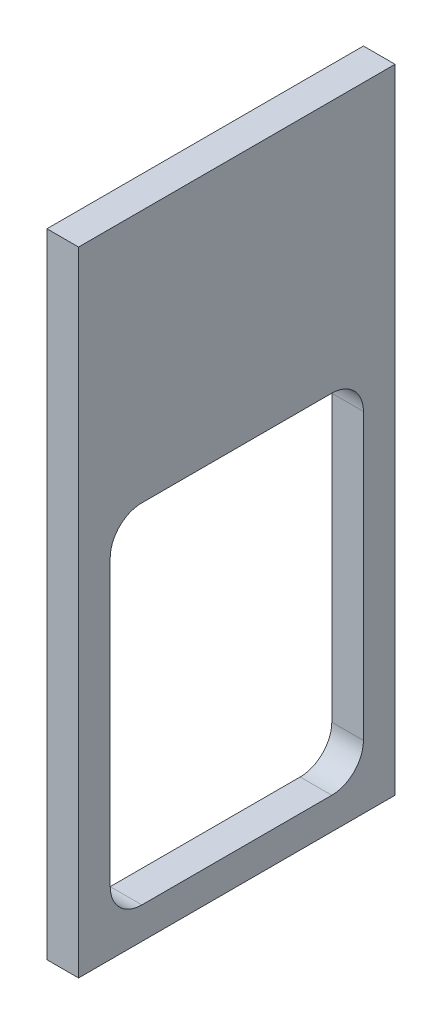
SolidWorks part; units mm, degrees
ref_plane "前视基准面" through (0, 0, 0) normal (0, 0, 1) x (1, 0, 0)
ref_plane "上视基准面" through (0, 0, 0) normal (0, 1, 0) x (1, 0, 0)
ref_plane "右视基准面" through (0, 0, 0) normal (1, 0, 0) x (0, 0, -1)
sketch "草图1" plane through (0, 0, 0) normal (1, 0, 0) x (0, 0, -1)
  line L1 (-50, -100) -> (50, -100)
  line L2 (-50, -100) -> (-50, 100)
  line L3 (-50, 100) -> (50, 100)
  line L4 (50, -100) -> (50, 100)
  line L5 (-50, -100) -> (50, 100) construction
  line L6 (-50, 100) -> (50, -100) construction
  point P0 (0, 0)
  dimension "D1" = 100
  dimension "D2" = 200
extrude "凸台-拉伸1" add sketch "草图1" along normal blind 10
sketch "草图2" plane through (10, 0, 0) normal (1, 0, 0) x (0, 0, -1)
  line L0 (50, -100) -> (50, 100) construction
  line L1 (-40, -90) -> (40, -90)
  line L2 (-40, -90) -> (-40, 20)
  line L3 (-40, 20) -> (40, 20)
  line L4 (40, -90) -> (40, 20)
  line L5 (-50, 100) -> (-50, -100) construction
  line L6 (-50, -100) -> (50, -100) construction
  line L7 (50, 100) -> (-50, 100) construction
  dimension "D1" = 10
  dimension "D2" = 10
  dimension "D3" = 10
  dimension "D4" = 80
extrude "切除-拉伸1" cut sketch "草图2" against normal through all
fillet "圆角1" radius 10 4 edges at (5, 20, 40) (5, 20, -40) (5, -90, -40) (5, -90, 40)
